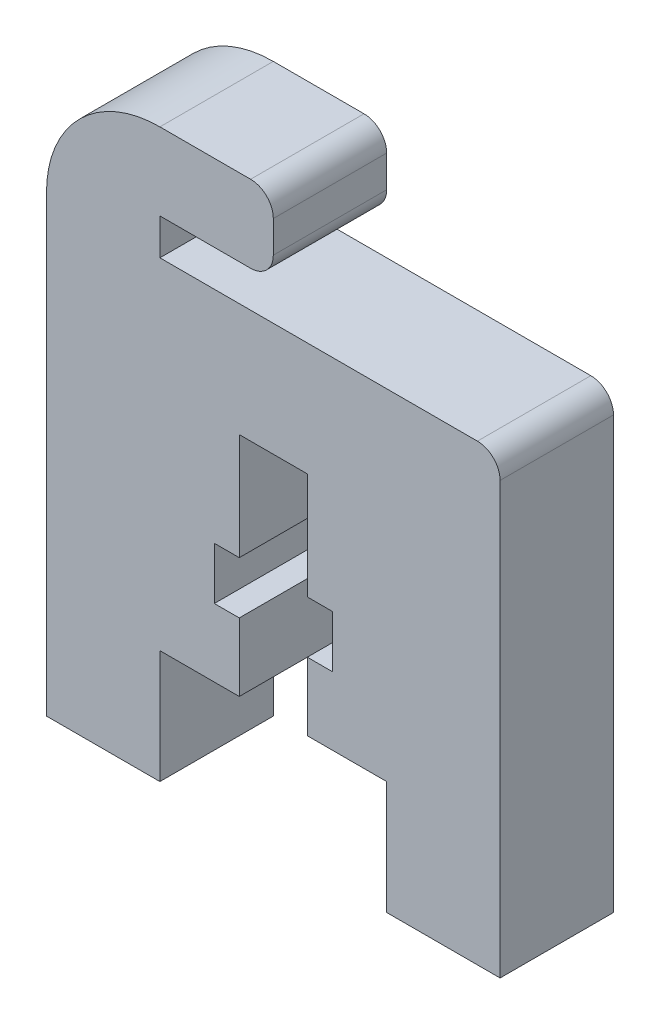
SolidWorks part; units mm, degrees
ref_plane "Front Plane" through (0, 0, 0) normal (0, 0, 1) x (1, 0, 0)
ref_plane "Top Plane" through (0, 0, 0) normal (0, 1, 0) x (1, 0, 0)
ref_plane "Right Plane" through (0, 0, 0) normal (1, 0, 0) x (0, 0, -1)
sketch "Sketch1" plane through (0, 0, 0) normal (0, 0, 1) x (1, 0, 0)
  line L0 (0, 5) -> (0, 19.9828)
  line L1 (20, 5) -> (20, 20)
  line L2 (20, 20) -> (5, 20)
  line L3 (5, 20) -> (5, 21.6)
  line L4 (5, 21.6) -> (10, 21.6)
  line L5 (10, 21.6) -> (10, 25)
  line L6 (10, 25) -> (0, 25)
  line L7 (0, 25) -> (0, 19.9828)
  line L8 (10, 5) -> (10, 16.2208) construction
  line L9 (8.5, 5) -> (5, 5)
  line L10 (5, 0) -> (0, 0)
  line L11 (0, 0) -> (0, 5)
  line L12 (5, 0) -> (5, 5)
  line L13 (11.5, 5) -> (15, 5)
  line L14 (15, 5) -> (15, 0)
  line L15 (15, 0) -> (20, 0)
  line L16 (20, 0) -> (20, 5)
  line L17 (8.5, 5) -> (11.5, 5) construction
  line L18 (11.5, 5) -> (11.5, 8)
  line L19 (11.5, 10.3) -> (12.6, 10.3)
  line L20 (7.4, 8) -> (7.4, 10.3)
  line L21 (12.6, 8) -> (11.5, 8)
  line L22 (11.5, 10.3) -> (11.5, 15)
  line L23 (11.5, 15) -> (8.5, 15)
  line L24 (8.5, 15) -> (8.5, 10.3)
  line L25 (8.5, 8) -> (7.4, 8)
  line L26 (12.6, 10.3) -> (12.6, 8)
  line L27 (7.4, 10.3) -> (8.5, 10.3)
  line L28 (8.5, 8) -> (8.5, 5)
  line L29 (10, 15) -> (10, 5) construction
  dimension "D1" = 1.6
  dimension "D2" = 20
  dimension "D3" = 5
  dimension "D4" = 3.4
  dimension "D5" = 10
  dimension "D6" = 5
  dimension "D7" = 5
  dimension "D8" = 5.2
  dimension "D9" = 3
  dimension "D10" = 2.3
  dimension "D11" = 3
  dimension "D12" = 10
  dimension "D13" = 10
extrude "Boss-Extrude1" add sketch "Sketch1" along normal blind 5
fillet "Fillet1" radius 5 1 edges at (0, 25, 2.5)
fillet "Fillet3" radius 1 2 edges at (20, 20, 2.5) (10, 21.6, 2.5)
fillet "Fillet4" radius 1 1 edges at (10, 25, 2.5)
